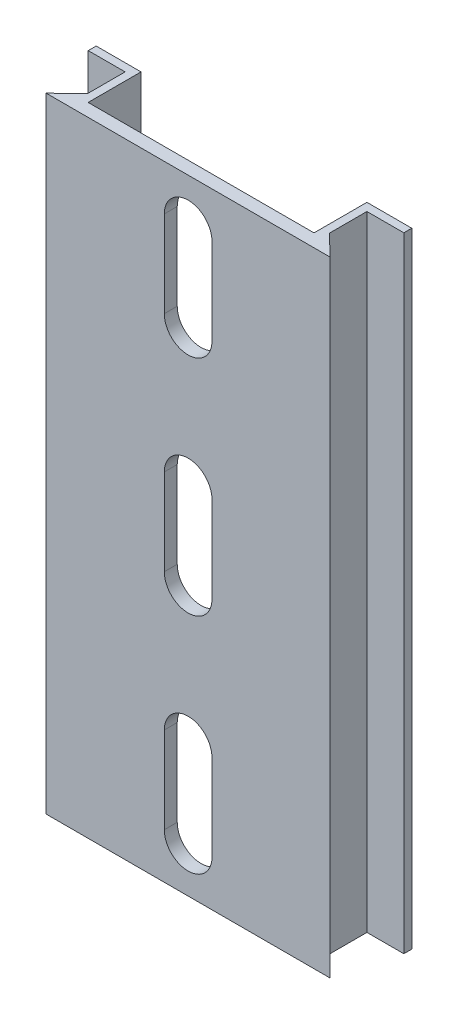
SolidWorks part; units mm, degrees
ref_plane "Front Plane" through (0, 0, 0) normal (0, 0, 1) x (1, 0, 0)
ref_plane "Top Plane" through (0, 0, 0) normal (0, 1, 0) x (1, 0, 0)
ref_plane "Right Plane" through (0, 0, 0) normal (1, 0, 0) x (0, 0, -1)
sketch "Sketch1" plane through (0, 0, 0) normal (0, 1, 0) x (1, 0, 0)
  line L0 (0, 0) -> (0, 1.4478)
  line L1 (-12.6365, 1.4478) -> (12.6365, 1.4478)
  line L2 (12.6365, 1.4478) -> (12.6365, 7.366)
  line L3 (12.6365, 7.366) -> (17.653, 7.366)
  line L4 (17.653, 7.366) -> (17.653, 6.477)
  line L5 (17.653, 6.477) -> (13.5255, 6.477)
  line L6 (13.5255, 6.477) -> (13.5255, 2.286)
  line L7 (13.5255, 2.286) -> (15.875, 0)
  line L8 (15.875, 0) -> (-15.875, 0)
  line L9 (-13.5255, 2.286) -> (-15.875, 0)
  line L10 (-13.5255, 6.477) -> (-13.5255, 2.286)
  line L11 (-17.653, 6.477) -> (-13.5255, 6.477)
  line L12 (-17.653, 7.366) -> (-17.653, 6.477)
  line L13 (-12.6365, 7.366) -> (-17.653, 7.366)
  line L14 (-12.6365, 1.4478) -> (-12.6365, 7.366)
  dimension "D1" = 15.875
  dimension "D2" = 13.5255
  dimension "D3" = 0.889
  dimension "D4" = 1.4478
  dimension "D5" = 7.366
  dimension "D6" = 0.889
  dimension "D7" = 2.286
  dimension "D8" = 17.653
extrude "Boss-Extrude1" add sketch "Sketch1" along normal mid plane 69.85 contours L1 L14 L13 L12 L11 L10 L9 L8 L0 | L8 L7 L6 L5 L4 L3 L2 L1 L0
sketch "Sketch2" plane through (0, 0, 0) normal (0, 0, 1) x (1, 0, 0)
  line L0 (0, -4.833) -> (0, 4.833) construction
  line L1 (-2.667, -4.833) -> (-2.667, 4.833)
  line L2 (2.667, -4.833) -> (2.667, 4.833)
  line L3 (-15.875, 0) -> (15.875, 0) construction
  line L4 (-15.875, 34.925) -> (-15.875, -34.925) construction
  line L5 (15.875, 34.925) -> (15.875, -34.925) construction
  arc A0 (-2.667, -4.833) -> (2.667, -4.833) centre (0, -4.833) ccw
  arc A1 (2.667, 4.833) -> (-2.667, 4.833) centre (0, 4.833) ccw
  point P3 (0, 0)
  point P15 (0, -7.5)
  point P16 (0, 7.5)
  dimension "D1" = 15
  dimension "D2" = 2.667
extrude "Cut-Extrude1" cut sketch "Sketch2" against normal through all
ref_plane "Plane1" through (0, 0, 0) normal (-1, 0, 0) x (0, 0, 1)
ref_plane "Plane2" through (0, 0, 0) normal (0, 1, 0) x (1, 0, 0)
pattern_linear "LPattern1" count 2 spacing 25 along (0, -1, 0) count 2 spacing 25 along (0, 1, 0) of "Cut-Extrude1"
